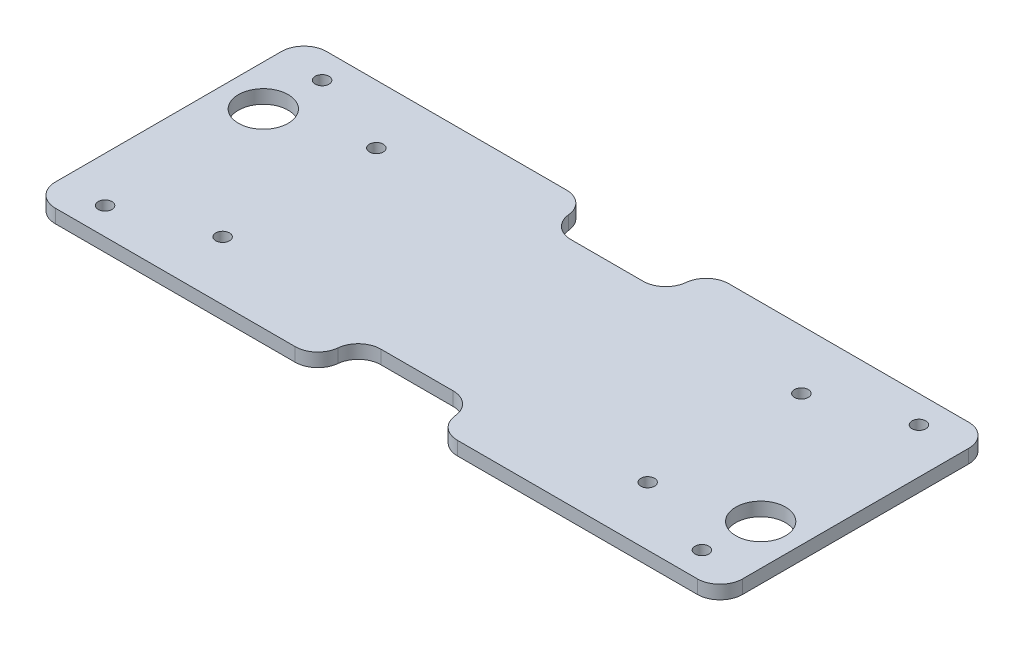
SolidWorks part; units mm, degrees
ref_plane "前视基准面" through (0, 0, 0) normal (0, 0, 1) x (1, 0, 0)
ref_plane "上视基准面" through (0, 0, 0) normal (0, 1, 0) x (1, 0, 0)
ref_plane "右视基准面" through (0, 0, 0) normal (1, 0, 0) x (0, 0, -1)
sketch "草图1" plane through (0, 0, 0) normal (0, 1, 0) x (1, 0, 0)
  line L1 (-76, 30) -> (76, 30)
  line L2 (-76, 30) -> (-76, -30)
  line L3 (-76, -30) -> (76, -30)
  line L4 (76, 30) -> (76, -30)
  line L5 (-76, 30) -> (76, -30) construction
  line L6 (-76, -30) -> (76, 30) construction
  point P0 (0, 0)
  dimension "D1" = 60
  dimension "D2" = 152
extrude "凸台-拉伸1" add sketch "草图1" along normal blind 3
fillet "圆角1" radius 5 4 edges at (-76, 1.5, -30) (76, 1.5, -30) (76, 1.5, 30) (-76, 1.5, 30)
sketch "草图2" plane through (0, 3, 0) normal (0, 1, 0) x (1, 0, 0)
  line L0 (0, 0) -> (0, -57.8505) construction
  line L1 (0, 0) -> (87.505, 0) construction
  line L2 (-71, -30) -> (71, -30) construction
  circle A0 centre (-66, -24) radius 1.525
  circle A1 centre (66, -24) radius 1.525
  circle A2 centre (66, 24) radius 1.525
  circle A3 centre (-66, 24) radius 1.525
  dimension "D1" = 3.05
  dimension "D2" = 66
  dimension "D3" = 6
extrude "切除-拉伸1" cut sketch "草图2" against normal up to next
sketch "草图3" plane through (0, 3, 0) normal (0, 1, 0) x (1, 0, 0)
  line L0 (0, 0) -> (0, -51.2695) construction
  line L1 (-71, -30) -> (71, -30) construction
  line L2 (-8, -21) -> (8, -21)
  line L3 (-8, -21) -> (-8, -30)
  line L4 (-8, -30) -> (8, -30)
  line L5 (8, -21) -> (8, -30)
  line L6 (-8, -21) -> (8, -30) construction
  line L7 (-8, -30) -> (8, -21) construction
  line L8 (0, 0) -> (81.1369, 0) construction
  line L9 (-8, 30) -> (8, 21) construction
  line L10 (-8, 21) -> (8, 30) construction
  line L11 (8, 21) -> (8, 30)
  line L12 (-8, 30) -> (8, 30)
  line L13 (-8, 21) -> (-8, 30)
  line L14 (-8, 21) -> (8, 21)
  arc A0 (-17.9499, -30) -> (-12.9749, -25.5) centre (-17.9499, -25) ccw
  arc A1 (-12.9749, -25.5) -> (-8, -21) centre (-8, -26) cw
  arc A2 (12.9749, -25.5) -> (8, -21) centre (8, -26) ccw
  arc A3 (17.9499, -30) -> (12.9749, -25.5) centre (17.9499, -25) cw
  arc A4 (17.9499, 30) -> (12.9749, 25.5) centre (17.9499, 25) ccw
  arc A5 (12.9749, 25.5) -> (8, 21) centre (8, 26) cw
  arc A6 (-12.9749, 25.5) -> (-8, 21) centre (-8, 26) ccw
  arc A7 (-17.9499, 30) -> (-12.9749, 25.5) centre (-17.9499, 25) cw
  point P1 (0, -25.5)
  point P33 (0, 25.5)
  line M5 (71, 30) -> (-71, 30)
  line M9 (-71, -30) -> (71, -30)
  dimension "D3" = 5
  dimension "D4" = 5
  dimension "D1" = 9
  dimension "D2" = 16
extrude "切除-拉伸2" cut sketch "草图3" against normal up to next contours A1 A0 L3 M9 | L5 L2 L3 M9 | A3 A2 L5 M9 | A7 A6 L13 M5 | L13 L14 L11 M5 | A5 A4 L11 M5
sketch "草图4" plane through (0, 3, 0) normal (0, 1, 0) x (1, 0, 0)
  line L0 (0, 0) -> (82.1036, 0) construction
  line L1 (0, 0) -> (0, 32.5673) construction
  line L2 (-71, -30) -> (-17.9499, -30) construction
  line L3 (-76, 25) -> (-76, -25) construction
  circle A0 centre (-47, -17) radius 1.525
  circle A2 centre (-47, 17) radius 1.525
  circle A3 centre (47, -17) radius 1.525
  circle A4 centre (47, 17) radius 1.525
  dimension "D1" = 3.05
  dimension "D2" = 13
  dimension "D3" = 29
extrude "切除-拉伸3" cut sketch "草图4" against normal up to next
sketch "草图5" plane through (0, 3, 0) normal (0, 1, 0) x (1, 0, 0)
  line L0 (-17.9499, 30) -> (-71, 30) construction
  line L1 (-76, 25) -> (-76, -25) construction
  line L2 (17.9499, -30) -> (71, -30) construction
  line L4 (76, -25) -> (76, 25) construction
  circle A0 centre (-67, 12) radius 5.5
  circle A1 centre (67, -12) radius 5.5
  point P12 (76, -5.2407)
  point P15 (76, -5.0324)
  dimension "D1" = 11
  dimension "D4" = 11
  dimension "D2" = 18
  dimension "D3" = 9
  dimension "D5" = 18
  dimension "D6" = 9
extrude "切除-拉伸4" cut sketch "草图5" against normal up to next
